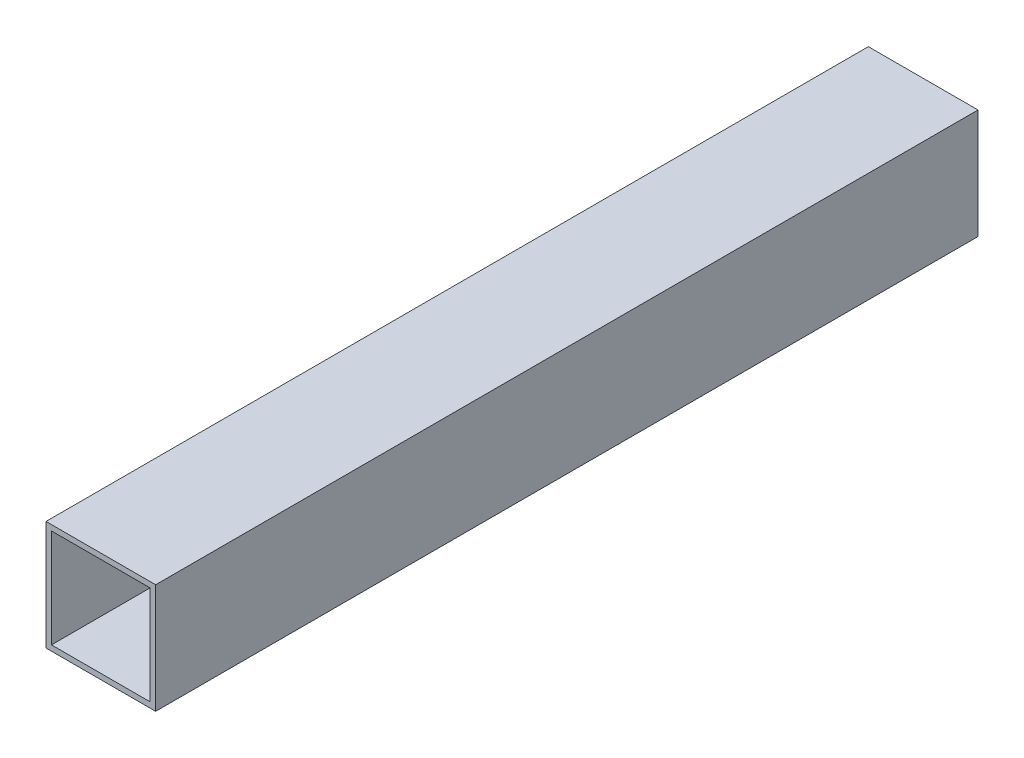
SolidWorks part; units mm, degrees
ref_plane "前视基准面" through (0, 0, 0) normal (0, 0, 1) x (1, 0, 0)
ref_plane "上视基准面" through (0, 0, 0) normal (0, 1, 0) x (1, 0, 0)
ref_plane "右视基准面" through (0, 0, 0) normal (1, 0, 0) x (0, 0, -1)
other "Configuration Table"
sketch "草图1" plane through (0, 0, 0) normal (0, 0, 1) x (1, 0, 0)
  line L0 (-9, 9) -> (9, 9)
  line L1 (-10, -10) -> (10, -10)
  line L2 (-10, -10) -> (-10, 10)
  line L3 (-10, 10) -> (10, 10)
  line L4 (10, -10) -> (10, 10)
  line L5 (-10, -10) -> (10, 10) construction
  line L6 (-10, 10) -> (10, -10) construction
  line L7 (9, -9) -> (9, 9)
  line L8 (-9, -9) -> (9, -9)
  line L9 (-9, -9) -> (-9, 9)
  point P0 (0, 0)
  dimension "D1" = 20
  dimension "D2" = 20
  dimension "D3" = 1
extrude "凸台-拉伸1" add sketch "草图1" along normal blind 150
